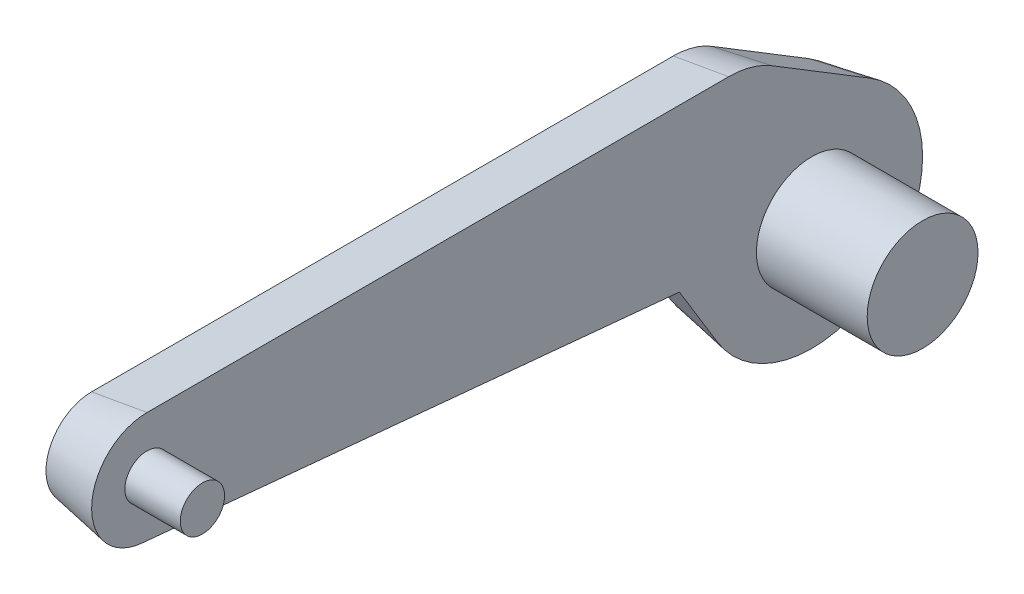
SolidWorks part; units mm, degrees
material "Plain Carbon Steel"
ref_plane "Front Plane" through (0, 0, 0) normal (0, 0, 1) x (1, 0, 0)
ref_plane "Top Plane" through (0, 0, 0) normal (0, 1, 0) x (1, 0, 0)
ref_plane "Right Plane" through (0, 0, 0) normal (1, 0, 0) x (0, 0, -1)
sketch "Sketch1" plane through (0, 0, 0) normal (1, 0, 0) x (0, 0, -1)
  circle A0 centre (0, 0) radius 250
  dimension "D1" = 500
extrude "Boss-Extrude1" add sketch "Sketch1" along normal mid plane 500
sketch "Sketch3" plane through (-250, 0, 0) normal (-1, 0, 0) x (0, 0, 1)
  line L0 (21.4466, 500) -> (0, 500) construction
  line L1 (0, 0) -> (375, 375) construction
  line L2 (3000, 500) -> (2750, 500) construction
  line L3 (-260.2588, 426.9255) -> (179.8059, 695.1941)
  line L4 (426.9255, -260.2588) -> (597.4899, 19.5331)
  line L5 (375, 750) -> (3000, 750)
  line L6 (597.4899, 19.5331) -> (3023.7557, 251.1312)
  line L7 (-140.3882, 500) -> (-811.2879, 500) construction
  arc A0 (21.2867, 499.5467) -> (0, 500) centre (0, 0) ccw
  arc A1 (3023.7557, 251.1312) -> (3000, 750) centre (3000, 500) ccw
  arc A2 (375, 750) -> (179.8059, 695.1941) centre (375, 375) ccw
  arc A3 (21.4466, 500) -> (21.2867, 499.5467) centre (375, 375) ccw
  arc A4 (-260.2588, 426.9255) -> (426.9255, -260.2588) centre (0, 0) ccw
  dimension "D1" = 1000
  dimension "D2" = 500
  dimension "D3" = 45
  dimension "D6" = 750
  dimension "D4" = 3000
  dimension "D5" = 500
extrude "Boss-Extrude4" add sketch "Sketch3" along normal blind 250 draft 10
sketch "Sketch5" plane through (-250, 0, 0) normal (1, 0, 0) x (0, 0, -1)
  circle A0 centre (-3000, 500) radius 100
  dimension "D1" = 200
extrude "Boss-Extrude6" add sketch "Sketch5" along normal blind 250
